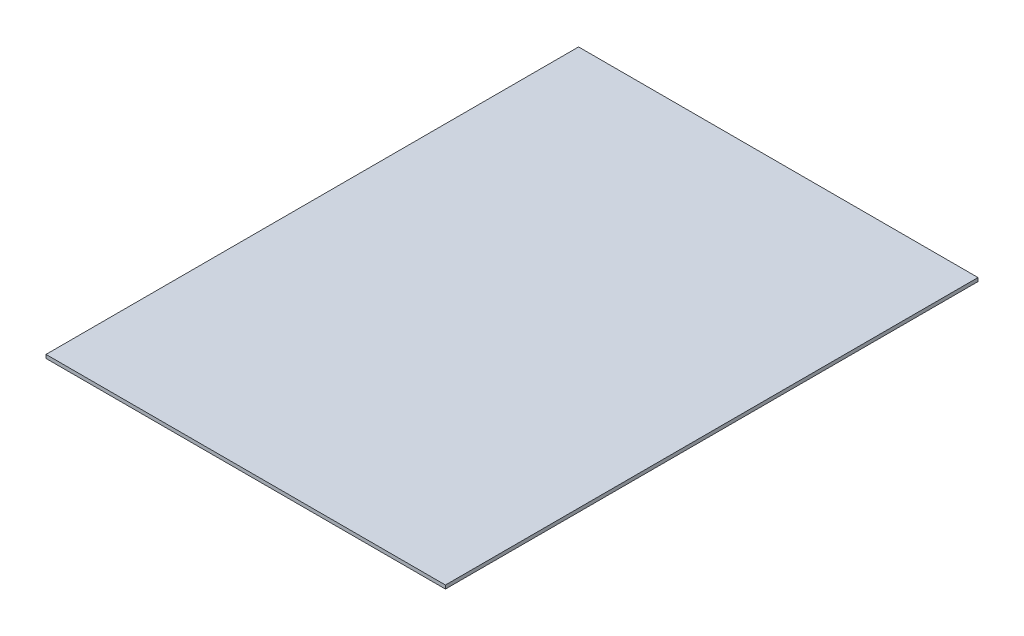
SolidWorks part; units mm, degrees
ref_plane "Front Plane" through (0, 0, 0) normal (0, 0, 1) x (1, 0, 0)
ref_plane "Top Plane" through (0, 0, 0) normal (0, 1, 0) x (1, 0, 0)
ref_plane "Right Plane" through (0, 0, 0) normal (1, 0, 0) x (0, 0, -1)
sketch "Sketch1" plane through (0, 0, 0) normal (0, 0, 1) x (1, 0, 0)
  line L0 (-304.8, 0) -> (304.8, 0) construction
  line L1 (0, -0.762) -> (0, 0.762) construction
  point P5 (0, 0)
  point P9 (0, 0)
  dimension "Width" = 609.6
  dimension "Thickness" = 1.524
sketch "Sketch2" plane through (0, 0, 0) normal (1, 0, 0) x (0, 0, -1)
  line L0 (-304.8, 0) -> (304.8, 0) construction
  point P3 (0, 0)
  dimension "Length" = 609.6
sketch "Sketch3" plane through (0, 0, 0) normal (0, 0, 1) x (1, 0, 0)
  line L1 (-304.8, -0.762) -> (304.8, -0.762)
  line L2 (-304.8, -0.762) -> (-304.8, 0.762)
  line L3 (-304.8, 0.762) -> (304.8, 0.762)
  line L4 (304.8, -0.762) -> (304.8, 0.762)
  line L5 (-304.8, -0.762) -> (304.8, 0.762) construction
  line L6 (-304.8, 0.762) -> (304.8, -0.762) construction
  point P0 (0, 0)
extrude "Boss-Extrude1" add sketch "Sketch3" along normal mid plane 609.6
sketch "Sketch4" plane through (0, 0, 0) normal (0, 1, 0) x (1, 0, 0)
  line L0 (-304.8, 0) -> (-209.55, 0)
  line L1 (209.55, 0) -> (304.8, 0)
  line L2 (0, 304.8) -> (0, 209.55)
  line L3 (0, -209.55) -> (0, -304.8)
  point P6 (304.8, -304.8)
  point P9 (-304.8, 304.8)
  point P10 (-209.55, 0)
  point P11 (0, -209.55)
  point P12 (209.55, 0)
  point P13 (304.8, 304.8)
  point P22 (0, 209.55)
  dimension "D1" = 95.25
sketch "Sketch5" plane through (0, 0, 0) normal (1, 0, 0) x (0, 0, -1)
  point P0 (304.8, 0.762)
  point P1 (304.8, -0.762)
sketch "Sketch6" plane through (0, 0.762, 0) normal (0, 1, 0) x (1, 0, 0)
  line L1 (-304.8, -304.8) -> (-133.35, -304.8)
  line L2 (-304.8, -304.8) -> (-304.8, -76.2)
  line L3 (-304.8, -76.2) -> (-133.35, -76.2)
  line L4 (-133.35, -304.8) -> (-133.35, -76.2)
  dimension "D1" = 171.45
  dimension "D2" = 228.6
extrude "Cut-Extrude1" cut sketch "Sketch6" against normal through all flip side to cut
equation "\"D1@Boss-Extrude1\"=\"Length@Sketch2\""
